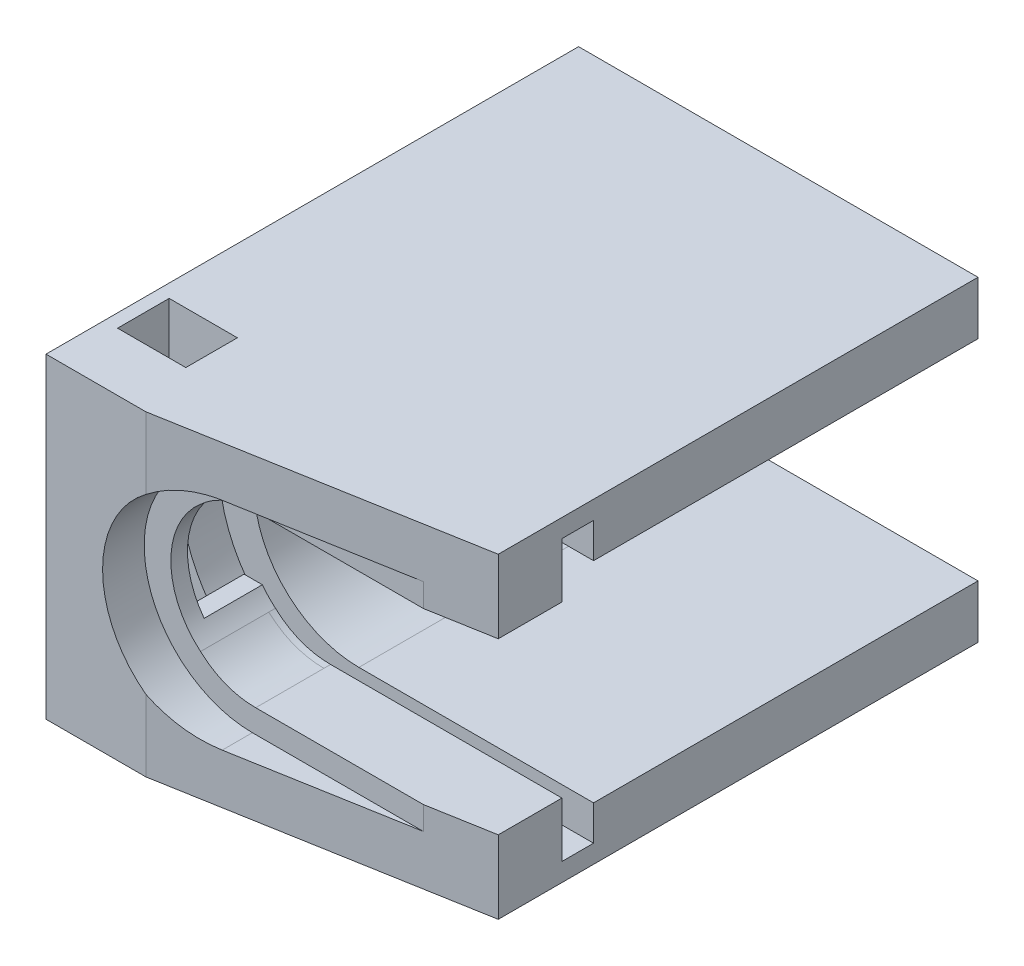
SolidWorks part; units mm, degrees
other "标注1"
sketch "草图10" plane through (24, 9.5, 31.5) normal (0.9281, 0.3391, 0.154) x (-0.3723, 0.8344, 0.4063)
other "标注2"
sketch "草图11" plane through (24, 9.5, 31.5) normal (0.9281, 0.3391, 0.154) x (-0.3723, 0.8344, 0.4063)
ref_plane "前视基准面" through (0, 0, 0) normal (1, 0, 0) x (0, 1, 0)
ref_plane "上视基准面" through (0, 0, 0) normal (0, 0, 1) x (0, 1, 0)
ref_plane "右视基准面" through (0, 0, 0) normal (0, 1, 0) x (-1, 0, 0)
other "Configuration Table"
sketch "1底部方形_24x19" plane through (0, 0, 0) normal (0, 0, 1) x (0, 1, 0)
  line L1 (-9.5, 12) -> (9.5, 12)
  line L2 (-9.5, 12) -> (-9.5, -12)
  line L3 (-9.5, -12) -> (9.5, -12)
  line L4 (9.5, 12) -> (9.5, -12)
  line L5 (0, -12) -> (0, 12) construction
  line L6 (-9.5, 0) -> (9.5, 0) construction
  point P0 (0, 0)
  dimension "D1" = 19
  dimension "D2" = 24
extrude "1凸台-拉伸_高33" add sketch "1底部方形_24x19" along normal blind 33
sketch "2吸嘴停靠渐变槽" plane through (0, 0, 33) normal (0, 0, 1) x (1, 0, 0)
  line L0 (12, -9.5) -> (12, 9.5) construction
  line L1 (-12, 9.5) -> (-12, -9.5) construction
  line L2 (12, -5.1) -> (12, 5.1)
  line L3 (-12, 9.5) -> (-12, -9.5) construction
  line L4 (-12, 0) -> (12, 0) construction
  line L5 (-1.9, 5.1) -> (12, 5.1)
  line L6 (-1.9, -5.1) -> (12, -5.1)
  line L7 (-5.2139, -3.8302) -> (-2, 0) construction
  line L8 (-5.2139, 3.8302) -> (-2, 0) construction
  line L9 (-4.0554, -4.6222) -> (-1.9, 0) construction
  line L10 (-1.9, 0) -> (-4.0554, 4.6222) construction
  arc A0 (-1.9, 5.1) -> (-1.9, -5.1) centre (-1.9, 0) ccw construction
  arc A1 (-5.2139, 3.8302) -> (-5.2139, -3.8302) centre (-2, 0) ccw
  circle A2 centre (-1.9, 0) radius 5.1 construction
  spline S0 degree 2 poles (-5.2139, 3.8302) (-3.8291, 5.0932) (-1.9, 5.1) knots 0 0 0 1 1 1
  spline S1 degree 2 poles (-5.2139, -3.8302) (-3.8291, -5.0932) (-1.9, -5.1) knots 0 0 0 1 1 1
  point P7 (-7, 0)
  point P14 (-5.2139, 3.8302)
  point P15 (-4.0554, 4.6222)
  point P16 (-4.0554, -4.6222)
  point P17 (-5.2139, -3.8302)
  dimension "D1" = 10.2
  dimension "D4" = 10
  dimension "D2" = 5
  dimension "D3" = 10.1
  dimension "D5" = 0.1
  dimension "D6" = 50
  dimension "D7" = 50
  dimension "D8" = 65
  dimension "D9" = 65
  dimension "D10" = 10.2
extrude "2切除-拉伸" cut sketch "2吸嘴停靠渐变槽" against normal up to next
ref_plane "3基准面1" through (0, 0, 25) normal (0, 0, 1) x (1, 0, 0)
sketch "4反光板停靠槽" plane through (0, 0, 25) normal (0, 0, 1) x (1, 0, 0)
  line L18 (-12, 9.5) -> (12, 9.5) construction
  line L22 (-0.7, 8.4) -> (12, 8.4)
  line L23 (12, -9.5) -> (12, 9.5) construction
  line L24 (-0.7, -8.4) -> (12, -8.4)
  line L25 (12, 8.4) -> (12, -8.4)
  line L27 (12, 0) -> (-12, 0) construction
  line L28 (-12, -9.5) -> (12, -9.5) construction
  arc A2 (-0.7, 8.4) -> (-0.7, -8.4) centre (-2, 0) ccw
  arc A5 (-5.2139, 3.8302) -> (-5.2139, -3.8302) centre (-2, 0) ccw construction
  arc A6 (-5.2139, 3.8302) -> (-5.2139, -3.8302) centre (-2, 0) ccw construction
  dimension "D1" = 9.5
  dimension "D2" = 17
  dimension "D5" = 8.4
  dimension "D6" = 5
  dimension "D7" = 9.5
  dimension "D3" = 16.8
  dimension "D4" = 8.4
extrude "4切除-拉伸2" cut sketch "4反光板停靠槽" against normal blind 1.9 contours L22 L25 L24 A2
ref_plane "5基准面_反光板下表面" through (0, 0, 23.1) normal (0, 0, 1) x (1, 0, 0)
sketch "6反光板小圆柱" plane through (0, 0, 23.1) normal (0, 0, 1) x (1, 0, 0)
  line L1 (-2.1, -6.3) -> (12, -6.3)
  line L5 (-2.1, 5.1) -> (-2.1, -5.1) construction
  line L6 (-2.1, 6.3) -> (12, 6.3)
  line L7 (12, 5.1) -> (12, 9.5) construction
  line L8 (12, 6.3) -> (12, -6.3)
  arc A2 (-2.1, 6.3) -> (-2.1, -6.3) centre (-2.1, 0) ccw
  point P0 (-2.1, 0)
  point P2 (-2, 0)
  point P13 (12, 0)
  dimension "D1" = 6.3
  dimension "D3" = 0.1
  dimension "D2" = 12.6
  dimension "D4" = 6.3
extrude "6切除-拉伸3" cut sketch "6反光板小圆柱" against normal up to next
sketch "7草图5" plane through (0, 0, 0) normal (0, 0, -1) x (1, 0, 0)
  line L0 (12, -9.5) -> (-12, -9.5) construction
  line L1 (-12, -9.5) -> (-12, 9.5) construction
  line L2 (-12, 9.5) -> (12, 9.5) construction
  line L3 (12, -9.5) -> (-12, -9.5)
  line L4 (-12, -9.5) -> (-12, 9.5)
  line L5 (-12, 9.5) -> (12, 9.5)
  line L6 (12, 9.5) -> (12, -9.5)
extrude "7凸台-拉伸_底板厚度" add sketch "7草图5" against normal blind 5
sketch "8中轴面" plane through (-12, 0, 0) normal (-1, 0, 0) x (0, -1, 0)
  line L0 (0, 33) -> (0, 0) construction
  line L1 (-9.5, 33) -> (9.5, 33) construction
  line L2 (-9.5, 0) -> (9.5, 0) construction
ref_plane "9中轴基准面" through (0, 0, 0) normal (0, 1, 0) x (1, 0, 0)
sketch "10设计脱离斜坡" plane through (0, 9.5, 0) normal (0, 1, 0) x (-1, 0, 0)
  line L2 (-12, 33) -> (-12, 0) construction
  line L3 (12, 33) -> (12, 0) construction
  line L5 (-12, 31.1627) -> (-12, 33)
  line L6 (10.45, 25) -> (-10.45, 25) construction
  line L9 (9, 33) -> (-12, 33)
  line L10 (-12, 31.1627) -> (9, 33)
  line L11 (-12, 33) -> (12, 33) construction
  dimension "D1" = 5
  dimension "D2" = 3
  dimension "D3" = 1.8373
  dimension "D4" = 24
  dimension "D5" = 6.1627
extrude "10切除-拉伸4" cut sketch "10设计脱离斜坡" against normal up to surface (19 mm away) up to face at (0, -9.5, 16.5)
sketch "11磁铁高度" plane through (-12, 0, 0) normal (-1, 0, 0) x (0, -1, 0)
  line L0 (-9.5, 33) -> (-9.5, 0) construction
  line L1 (-9.5, 28.5) -> (-1, 28.5)
  line L2 (-9.5, 28.5) -> (-9.5, 25.4)
  line L3 (-9.5, 25.4) -> (-1, 25.4)
  line L4 (9.5, 28.5) -> (9.5, 25.4)
  line L5 (-9.5, 28.5) -> (9.5, 25.4) construction
  line L6 (-9.5, 25.4) -> (9.5, 28.5) construction
  line L7 (9.5, 33) -> (9.5, 0) construction
  line L8 (-1, 28.5) -> (-1, 25.4)
  line L9 (1, 28.5) -> (1, 25.4)
  line L10 (1, 28.5) -> (9.5, 28.5)
  line L11 (1, 25.4) -> (9.5, 25.4)
  line L15 (9.5, 0) -> (-9.5, 0) construction
  point P4 (0, 26.95)
  dimension "D1" = 28.5
  dimension "D2" = 3.1
  dimension "D3" = 1
  dimension "D4" = 1
extrude "11切除-拉伸5" cut sketch "11磁铁高度" against normal blind 4.9
sketch "11d1_磁铁开窗" plane through (-12, 0, 0) normal (-1, 0, 0) x (0, -1, 0)
  line L0 (1, 25.4) -> (9.5, 25.4) construction
  line L5 (-1, 28.5) -> (1, 25.4) construction
  line L7 (1, 28.5) -> (1, 25.4) construction
  line L8 (9.5, 28.5) -> (1, 28.5) construction
  line L9 (-3, 25.4) -> (3, 25.4)
  line L10 (-3, 25.4) -> (-3, 28.5)
  line L11 (-3, 28.5) -> (3, 28.5)
  line L12 (3, 25.4) -> (3, 28.5)
  line L13 (0, 28.5) -> (0, 25.4) construction
  line L14 (-3, 26.95) -> (3, 26.95) construction
  point P10 (0, 26.95)
  dimension "D1" = 6
extrude "11d1切除-拉伸6" cut sketch "11d1_磁铁开窗" against normal blind 10
sketch "12切除薄壁" plane through (0, 0, 25.4) normal (0, 0, 1) x (1, 0, 0)
  line L43 (-0.7, 8.4) -> (-0.7, -8.4)
  arc A0 (-0.7, 8.4) -> (-0.7, -8.4) centre (-2, 0) ccw construction
  arc A7 (-0.7, 8.4) -> (-0.7, -8.4) centre (-2, 0) ccw
extrude "12切除-拉伸9" cut sketch "12切除薄壁" against normal up to next
sketch "螺丝安装孔" plane through (0, 0, 5) normal (0, 0, 1) x (1, 0, 0)
  line L0 (13.2, 0) -> (-13.2, 0) construction
  line L1 (12, 6.3) -> (12, -6.3) construction
  circle A0 centre (2, 0) radius 3.5
  dimension "D1" = 10
  dimension "D2" = 7
sketch "设计内套槽" plane through (0, 0, 33) normal (0, 0, 1) x (1, 0, 0)
  line L0 (-2.1, 6.5) -> (12, 6.5)
  line L2 (-2.1, -6.5) -> (12, -6.5)
  line L4 (12, 6.5) -> (12, -6.5)
  line L5 (12, -9.5) -> (12, 9.5) construction
  arc A1 (-1.4745, -4.9607) -> (-1.4745, 4.9607) centre (-2.1, 0) ccw construction
  arc A2 (-2.1, 6.5) -> (-2.1, -6.5) centre (-2.1, 0) ccw
  point P4 (-2.1, 0)
  point P8 (-2, 0)
  dimension "D1" = 13
  dimension "D4" = 6.5
  dimension "D6" = 5
  dimension "D5" = 0.1
  dimension "D2" = 6.5
  dimension "D3" = 6.5
extrude "切除-拉伸11" cut sketch "设计内套槽" against normal blind 3.5 contours L0 A2 L2 L4
sketch "实际高度" plane through (0, 0, 33) normal (0, 0, 1) x (1, 0, 0)
  line L0 (-9, -9.5) -> (-9, 9.5) construction
  line L1 (41.98, 9.5) -> (-12, 9.5)
  line L2 (41.98, 9.5) -> (41.98, -9.5)
  line L3 (41.98, -9.5) -> (-12, -9.5)
  line L4 (-12, 9.5) -> (-12, -9.5)
  line L5 (41.98, 9.5) -> (-12, -9.5) construction
  line L6 (41.98, -9.5) -> (-12, 9.5) construction
  line L7 (-9, 9.5) -> (-12, 9.5) construction
  point P4 (14.99, 0)
  dimension "D1" = 23.99
extrude "切除-拉伸12" cut sketch "实际高度" against normal blind 1
sketch "实际脱离斜坡" plane through (0, -9.5, 0) normal (0, -1, 0) x (1, 0, 0)
  line L0 (2.4301, 32) -> (12, 31.1627) construction
  line L1 (2.4301, 32) -> (12, 31.1627)
  line L3 (-6, 32) -> (12, 28.8261)
  line L5 (-12, 32) -> (2.4301, 32) construction
  line L6 (12, 31.1627) -> (12, 0) construction
  line L7 (10.45, 25) -> (-10.45, 25) construction
  line L9 (-12, 33) -> (-12, 0) construction
  line L11 (12, 28.8261) -> (12, 31.1627)
  line L12 (2.4301, 32) -> (-6, 32)
  dimension "D1" = 6
  dimension "D2" = 10
  dimension "D3" = 3.8261
  dimension "D4" = 3.1739
  dimension "D5" = 18
extrude "切除-拉伸13" cut sketch "实际脱离斜坡" against normal through all
extrude "切除-拉伸15" cut sketch "螺丝安装孔" against normal up to next contours A0
sketch "退刀中心位置" plane through (0, 0, 5) normal (0, 0, 1) x (1, 0, 0)
  line L0 (12, -9.5) -> (12, 9.5) construction
  line L1 (12, -9.5) -> (12, 9.5) construction
  line L2 (12, 0) -> (-12, 0) construction
  line L3 (27.5479, 0) -> (-12, 0) construction
  line L4 (13.2, 0) -> (-13.2, 0) construction
  line L5 (20, 0) -> (20, -11.3299) construction
  circle A0 centre (20, 0) radius 8 construction
  dimension "D2" = 16
  dimension "D1" = 8
sketch "反光板槽_补缺" plane through (0, 0, 25.4) normal (0, 0, -1) x (1, 0, 0)
  line L0 (-7.1, -3) -> (-7.1, -6.8) construction
  line L1 (-0.7, -8.4) -> (-0.7, -5.1) construction
  line L2 (-0.7, -5.1) -> (-1.9, -5.1) construction
  line L3 (-6, -3) -> (-7.1, -3) construction
  line L4 (-7.1, 3) -> (-6, 3) construction
  line L5 (-1.9, 5.1) -> (-0.7, 5.1) construction
  line L6 (-0.7, 5.1) -> (-0.7, 8.4) construction
  line L7 (-7.1, 6.8) -> (-7.1, 3) construction
  line L8 (-7.1, -3) -> (-7.1, -6.8)
  line L9 (-0.7, -8.4) -> (-0.7, -5.1)
  line L10 (-0.7, -5.1) -> (-1.9, -5.1)
  line L11 (-6, -3) -> (-7.1, -3)
  line L12 (-7.1, 3) -> (-6, 3)
  line L13 (-1.9, 5.1) -> (-0.7, 5.1)
  line L14 (-0.7, 5.1) -> (-0.7, 8.4)
  line L15 (-7.1, 6.8) -> (-7.1, 3)
  arc A0 (-7.1, -6.8) -> (-0.7, -8.4) centre (-2, 0) ccw construction
  arc A1 (-6, -3) -> (-5.2139, -3.8302) centre (-2, 0) ccw construction
  arc A2 (-5.2139, 3.8302) -> (-6, 3) centre (-2, 0) ccw construction
  arc A3 (-0.7, 8.4) -> (-7.1, 6.8) centre (-2, 0) ccw construction
  arc A4 (-7.1, -6.8) -> (-0.7, -8.4) centre (-2, 0) ccw
  arc A5 (-6, -3) -> (-5.2139, -3.8302) centre (-2, 0) ccw
  arc A6 (-5.2139, 3.8302) -> (-6, 3) centre (-2, 0) ccw
  arc A7 (-0.7, 8.4) -> (-7.1, 6.8) centre (-2, 0) ccw
  parabola Q0 (-1.9, -5.1) -> (-5.2139, -3.8302) focus (-2.9632, -2.5982) apex (-3.8759, -4.7046) construction
  parabola Q1 (-5.2139, 3.8302) -> (-1.9, 5.1) focus (-2.9632, 2.5982) apex (-3.8759, 4.7046) construction
  parabola Q2 (-1.9, -5.1) -> (-5.2139, -3.8302) focus (-2.9632, -2.5982) apex (-3.8759, -4.7046)
  parabola Q3 (-5.2139, 3.8302) -> (-1.9, 5.1) focus (-2.9632, 2.5982) apex (-3.8759, 4.7046)
extrude "凸台-拉伸2" add sketch "反光板槽_补缺" along normal up to surface (0.4 mm away) up to face at (5.65, 6.75, 25)
sketch "磁铁宽度挡板" plane through (0, -9.5, 0) normal (0, -1, 0) x (1, 0, 0)
  line L0 (-7.1, 25.4) -> (-12, 25.4) construction
  line L1 (-12, 28.5) -> (-11.2, 28.5)
  line L2 (-12, 28.5) -> (-12, 25.4)
  line L3 (-12, 25.4) -> (-11.2, 25.4)
  line L4 (-11.2, 28.5) -> (-11.2, 25.4)
  line L5 (-12, 28.5) -> (-11.2, 25.4) construction
  line L6 (-12, 25.4) -> (-11.2, 28.5) construction
  line L7 (-7.1, 25.4) -> (-7.1, 28.5) construction
  point P4 (-11.6, 26.95)
  dimension "D1" = 4.1
  dimension "D2" = 0.8
extrude "凸台-拉伸3" add sketch "磁铁宽度挡板" against normal up to surface (19 mm away) up to face at (-4.9111, 9.5, 22.2918)
sketch "草图13" plane through (0, 0, 5) normal (0, 0, 1) x (1, 0, 0)
  line L3 (-2.1, -6.3) -> (12, -6.3)
  line L4 (12, -6.3) -> (12, 6.3)
  line L5 (12, 6.3) -> (-2.1, 6.3)
  line L6 (-2.1, -6.3) -> (12, -6.3)
  line L7 (12, -6.3) -> (12, 6.3)
  line L8 (12, 6.3) -> (-2.1, 6.3)
  arc A1 (-2.1, 6.3) -> (-2.1, -6.3) centre (-2.1, 0) ccw
  arc A2 (-2.1, 6.3) -> (-2.1, -6.3) centre (-2.1, 0) ccw
  dimension "D1" = 0
extrude "切除-拉伸16" cut sketch "草图13" against normal through all
